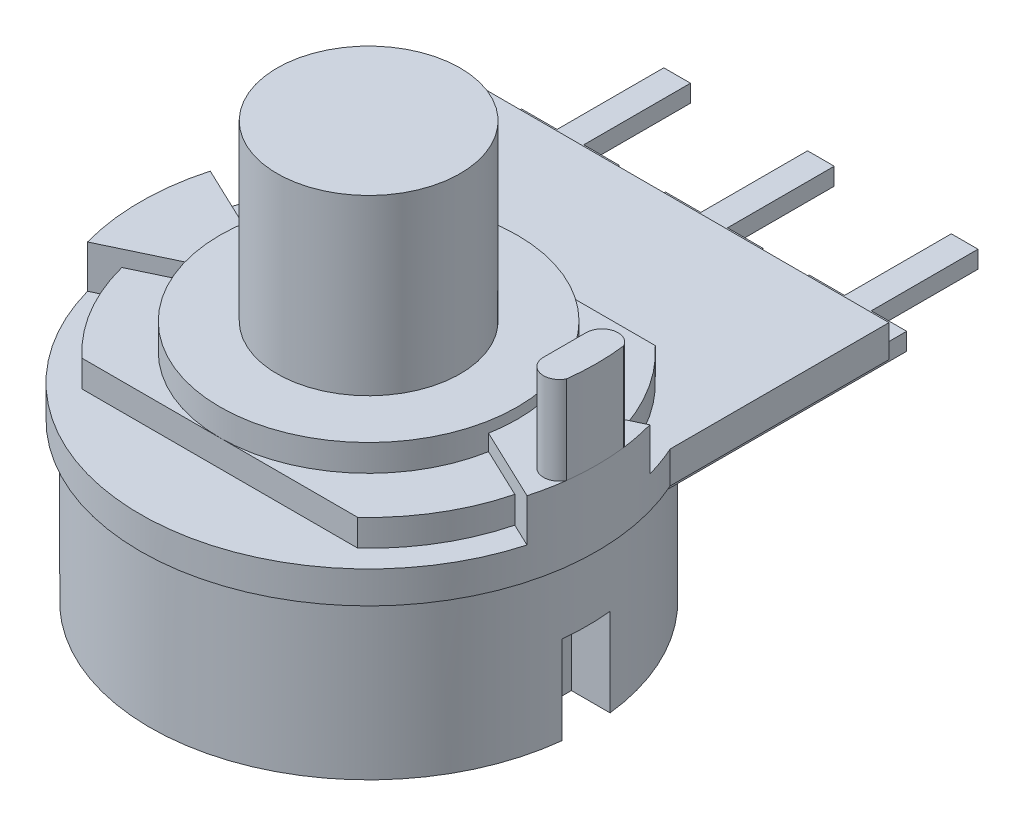
SolidWorks part; units mm, degrees
ref_plane "Front" through (0, 0, 0) normal (0, 0, 1) x (1, 0, 0)
ref_plane "Top" through (0, 0, 0) normal (0, 1, 0) x (1, 0, 0)
ref_plane "Right" through (0, 0, 0) normal (1, 0, 0) x (0, 0, -1)
sketch "Sketch1" plane through (0, 0, 0) normal (0, 1, 0) x (1, 0, 0)
  line L0 (-8.19, 0) -> (0, 0) construction
  line L1 (0, 8.19) -> (0, -8.19) construction
  line L2 (6.6904, -0.8935) -> (6.6904, 0.9065)
  line L3 (8.1904, 0.9065) -> (6.6904, 0.9065)
  line L6 (8.1411, -0.8935) -> (6.6904, -0.8935)
  arc A0 (8.1397, 0.9065) -> (8.1411, -0.8935) centre (0, 0) ccw
  dimension "D1" = 16.38
  dimension "D3" = 1.5
  dimension "D4" = 1.8
extrude "Boss-Extrude1" add sketch "Sketch1" along normal blind 3.3 contours L3 A0 L6 L2
sketch "Sketch2" plane through (0, 3.3, 0) normal (0, 1, 0) x (1, 0, 0)
  circle A0 centre (0, 0) radius 8.19
  dimension "D1" = 16.38
extrude "Boss-Extrude2" add sketch "Sketch2" along normal blind 2.6
sketch "Sketch3" plane through (0, 5.9, 0) normal (0, 1, 0) x (1, 0, 0)
  line L3 (7.8, 3.5018) -> (7.8, 11.7) construction
  line L6 (7.8, 11.7) -> (-7.8, 11.7)
  line L7 (7.8, 11.7) -> (7.8, 3.5018)
  line L9 (-7.8, 11.7) -> (-7.8, 3.5018)
  arc A0 (-7.8, 3.5018) -> (7.8, 3.5018) centre (0, 0) ccw
  dimension "D1" = 17.1
extrude "Boss-Extrude3" add sketch "Sketch3" along normal blind 1.2
sketch "Sketch4" plane through (0, 7.1, 0) normal (0, 1, 0) x (1, 0, 0)
  line L0 (8.55, 0) -> (7.6, 0) construction
  line L1 (0, 0) -> (0, 5.575) construction
  line L2 (5.1652, 5.575) -> (-5.1652, 5.575)
  line L3 (-7.6, 0) -> (7.6, 0) construction
  line L4 (5.1652, -5.575) -> (-5.1652, -5.575)
  arc A0 (-7.8, 3.5018) -> (7.8, 3.5018) centre (0, 0) ccw construction
  arc A1 (-5.1652, 5.575) -> (-5.1652, -5.575) centre (0, 0) ccw
  arc A2 (5.1652, -5.575) -> (5.1652, 5.575) centre (0, 0) ccw
  dimension "D1" = 0.95
  dimension "D2" = 5.575
extrude "Boss-Extrude4" add sketch "Sketch4" along normal blind 1
sketch "Sketch6" plane through (0, 7.1, 0) normal (0, 1, 0) x (1, 0, 0)
  line L0 (8.55, 0) -> (-8.55, 0) construction
  line L1 (8.55, 0) -> (8.55, 2.3) construction
  line L2 (0, 0) -> (3.4, 0) construction
  line L3 (8.2348, 2.3) -> (5.486, 0.9923)
  line L4 (5.486, -0.9923) -> (8.2348, -2.3)
  line L5 (0, 0) -> (0, -8.55) construction
  line L6 (-5.486, -0.9923) -> (-8.2348, -2.3)
  line L7 (-8.2348, 2.3) -> (-5.486, 0.9923)
  arc A0 (-7.8, 3.5018) -> (7.8, 3.5018) centre (0, 0) ccw construction
  arc A1 (-8.2348, 2.3) -> (-8.2348, -2.3) centre (0, 0) ccw
  arc A2 (-5.486, 0.9923) -> (-5.486, -0.9923) centre (0, 0) ccw
  arc A3 (8.2348, -2.3) -> (8.2348, 2.3) centre (0, 0) ccw
  arc A4 (5.486, -0.9923) -> (5.486, 0.9923) centre (0, 0) ccw
  dimension "D1" = 2.3
  dimension "D2" = 3.4
sketch "Sketch7" plane through (0, 8.1, 0) normal (0, 1, 0) x (1, 0, 0)
  circle A0 centre (0, 0) radius 5.575
extrude "Boss-Extrude5" add sketch "Sketch7" along normal blind 1
extrude "Boss-Extrude6" add sketch "Sketch6" along normal blind 1.6
sketch "Sketch8" plane through (0, 8.7, 0) normal (0, 1, 0) x (1, 0, 0)
  line L0 (8.55, 0) -> (7.35, 0) construction
  line L1 (8.55, 0) -> (8.55, 1.3962) construction
  line L2 (7.35, 1.3962) -> (8.55, 1.3962) construction
  line L3 (7.35, 0.7961) -> (8.55, 0.7961) construction
  line L4 (7.35, 1.3962) -> (7.35, 0.7961) construction
  line L6 (7.35, 0.7961) -> (7.35, -0.7961)
  arc A0 (8.4825, -1.0728) -> (8.4825, 1.0728) centre (0, 0) ccw
  arc A1 (7.35, 0.7961) -> (8.4825, 1.0728) centre (7.95, 0.7961) cw
  arc A2 (7.35, -0.7961) -> (8.4825, -1.0728) centre (7.95, -0.7961) ccw
extrude "Boss-Extrude7" add sketch "Sketch8" along normal blind 3.3
sketch "Sketch9" plane through (0, 9.1, 0) normal (0, 1, 0) x (1, 0, 0)
  circle A0 centre (0, 0) radius 3.43
  dimension "D1" = 6.86
extrude "Boss-Extrude8" add sketch "Sketch9" along normal blind 6.5
sketch "Sketch13" plane through (0, 5.9, 0) normal (0, -1, 0) x (1, 0, 0)
  line L0 (0, -11.7) -> (1.825, -11.7) construction
  line L1 (7.8, -11.7) -> (-7.8, -11.7) construction
  line L2 (1.825, -11.7) -> (1.825, -7.9841) construction
  line L3 (0, -11.7) -> (-1.83, -11.7) construction
  line L4 (1.825, -11.7) -> (1.825, -12.95) construction
  line L5 (-0.0025, -12.95) -> (0.4975, -12.95) construction
  line L7 (1.825, -7.9841) -> (1.825, -12.95)
  line L8 (1.825, -12.95) -> (0.4975, -12.95)
  line L9 (-1.83, -7.9829) -> (-1.83, -12.95)
  line L10 (0.4975, -12.95) -> (-0.5025, -12.95) construction
  line L11 (0.4975, -12.95) -> (0.4975, -16.95) construction
  line L12 (-0.5025, -12.95) -> (-1.83, -12.95)
  line L13 (0.4975, -16.95) -> (-0.5025, -16.95)
  line L14 (0.4975, -16.95) -> (0.4975, -12.95)
  line L15 (4.8847, -16.95) -> (4.8847, -12.95)
  line L16 (-0.5025, -16.95) -> (-0.5025, -12.95)
  line L17 (4.8847, -12.95) -> (3.5572, -12.95)
  line L19 (3.5572, -7.3772) -> (3.5572, -12.95)
  line L20 (7.2122, -12.95) -> (5.8847, -12.95)
  line L21 (5.8847, -16.95) -> (4.8847, -16.95)
  line L22 (7.2122, -3.8808) -> (7.2122, -12.95)
  line L23 (5.8847, -16.95) -> (5.8847, -12.95)
  line L24 (7.2122, -11.7) -> (7.8, -11.7) construction
  line L25 (7.2122, -11.7) -> (7.2122, -12.95) construction
  line L26 (-0.0025, -3.7) -> (-0.0025, -6.3521) construction
  line L27 (-5.8897, -16.95) -> (-4.8897, -16.95)
  line L28 (-5.8897, -16.95) -> (-5.8897, -12.95)
  line L29 (-4.8897, -16.95) -> (-4.8897, -12.95)
  line L30 (-4.8897, -12.95) -> (-3.5622, -12.95)
  line L31 (-7.2172, -12.95) -> (-5.8897, -12.95)
  line L32 (-7.2172, -3.8715) -> (-7.2172, -12.95)
  line L33 (-3.5622, -7.3748) -> (-3.5622, -12.95)
  arc A0 (-1.83, -7.9829) -> (1.825, -7.9841) centre (0, 0) ccw
  arc A1 (3.5572, -7.3772) -> (7.2122, -3.8808) centre (0, 0) ccw
  arc A2 (-7.2172, -3.8715) -> (-3.5622, -7.3748) centre (0, 0) ccw
  dimension "D1" = 1.825
  dimension "D3" = 1.25
  dimension "D4" = 0.5
  dimension "D5" = 1
  dimension "D6" = 4
extrude "Boss-Extrude9" add sketch "Sketch13" along normal blind 0.65
